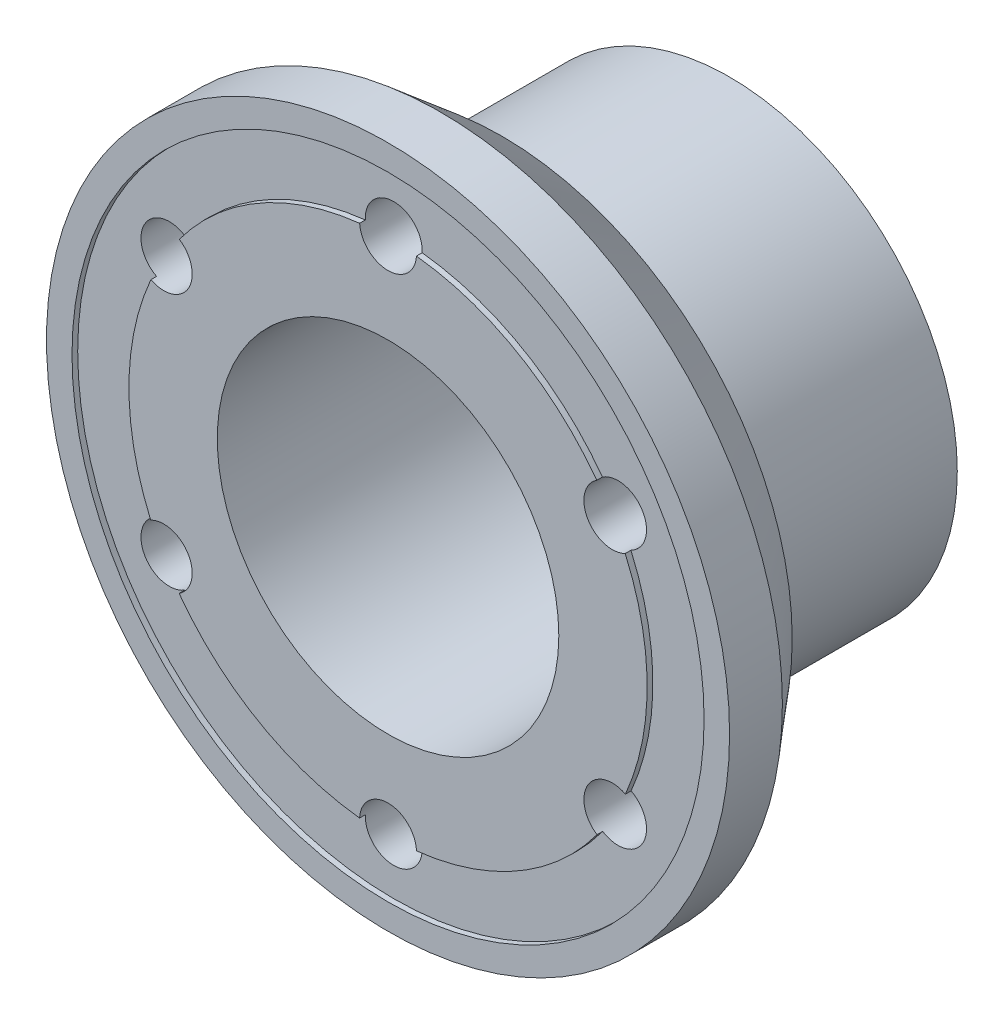
SolidWorks part; units mm, degrees
ref_plane "Front Plane" through (0, 0, 0) normal (0, 0, 1) x (1, 0, 0)
ref_plane "Top Plane" through (0, 0, 0) normal (0, 1, 0) x (1, 0, 0)
ref_plane "Right Plane" through (0, 0, 0) normal (1, 0, 0) x (0, 0, -1)
sketch "Sketch1" plane through (0, 0, 0) normal (0, 0, 1) x (1, 0, 0)
  circle A0 centre (0, 0) radius 40
  circle A1 centre (0, 0) radius 60
  circle A2 centre (0, 0) radius 27.5
extrude "Boss-Extrude1" add sketch "Sketch1" along normal blind 40 contours A2 | A0
sketch "Sketch3" plane through (0, 0, 40) normal (0, 0, 1) x (1, 0, 0)
  circle A0 centre (0, 0) radius 60
extrude "Boss-Extrude2" add sketch "Sketch3" along normal blind 20
sketch "Sketch4" plane through (0, 0, 60) normal (0, 0, 1) x (1, 0, 0)
  circle A0 centre (0, 0) radius 30
  circle A1 centre (0, 45.5416) radius 5
  circle A2 centre (39.4042, 22.7916) radius 5
  circle A3 centre (39.4042, -22.7084) radius 5
  circle A4 centre (0, -45.4584) radius 5
  circle A5 centre (-39.4042, -22.7084) radius 5
  circle A6 centre (-39.4042, 22.7916) radius 5
  point P18 (0, 0.0416)
  dimension "D1" = 6
extrude "Cut-Extrude2" cut sketch "Sketch4" against normal blind 90
chamfer "Chamfer2" distance 9 angle 50 1 edges at (60, 0, 40)
sketch "Sketch6" plane through (0, 0, 60) normal (0, 0, 1) x (1, 0, 0)
  circle A0 centre (0, 0) radius 45.5208
extrude "Cut-Extrude-Thin2" cut sketch "Sketch6" along normal blind 2 and the other way blind 1 thin
